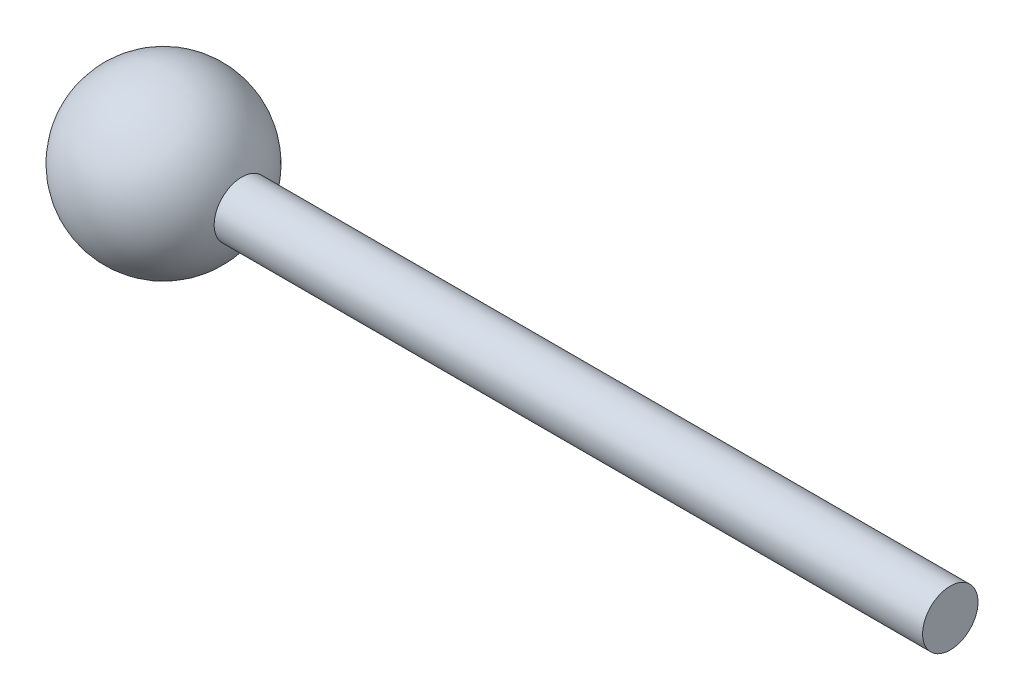
SolidWorks part; units mm, degrees
ref_plane "Front Plane" through (0, 0, 0) normal (0, 0, 1) x (1, 0, 0)
ref_plane "Top Plane" through (0, 0, 0) normal (0, 1, 0) x (1, 0, 0)
ref_plane "Right Plane" through (0, 0, 0) normal (1, 0, 0) x (0, 0, -1)
sketch "Sketch1" plane through (0, 0, 0) normal (0, 0, 1) x (1, 0, 0)
  line L0 (-19.05, 0) -> (19.05, 0)
  arc A0 (19.05, 0) -> (-19.05, 0) centre (0, 0) ccw
  dimension "D1" = 19.05
revolve "Revolve1" add sketch "Sketch1" angle 360 about L0
sketch "Sketch2" plane through (0, 0, 0) normal (1, 0, 0) x (0, 0, -1)
  circle A0 centre (0, 0) radius 6.35
  dimension "D1" = 12.7
extrude "Boss-Extrude1" add sketch "Sketch2" along normal blind 180.34
